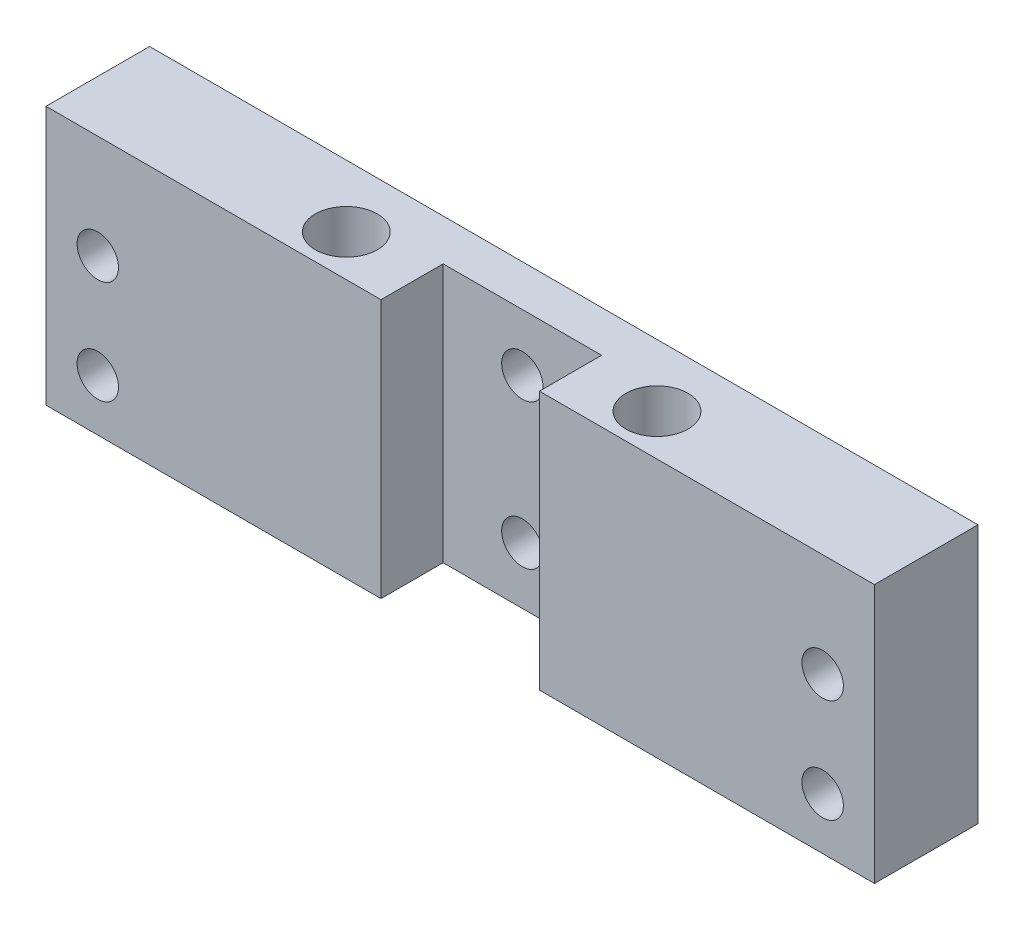
SolidWorks part; units mm, degrees
ref_plane "Plan de face" through (0, 0, 0) normal (0, 0, 1) x (1, 0, 0)
ref_plane "Plan de dessus" through (0, 0, 0) normal (0, 1, 0) x (1, 0, 0)
ref_plane "Plan de droite" through (0, 0, 0) normal (1, 0, 0) x (0, 0, -1)
sketch "Esquisse1" plane through (0, 0, 0) normal (0, 0, 1) x (1, 0, 0)
  line L0 (5, 25) -> (5, 0) construction
  line L1 (0, 0) -> (80, 0)
  line L2 (0, 0) -> (0, 25)
  line L3 (0, 25) -> (80, 25)
  line L4 (80, 0) -> (80, 25)
  line L5 (75, 0) -> (75, 25) construction
  line L6 (40, 25) -> (40, 0) construction
  circle A0 centre (5, 15) radius 2
  circle A1 centre (5, 5) radius 2
  circle A3 centre (75, 15) radius 2
  circle A4 centre (75, 5) radius 2
  circle A6 centre (40, 19.5) radius 2
  circle A7 centre (40, 5.5) radius 2
  point P29 (40, 12.5)
  dimension "D5" = 4
  dimension "D11" = 4
  dimension "D12" = 14
  dimension "D8" = 4
  dimension "D1" = 80
  dimension "D2" = 25
  dimension "D3" = 5
  dimension "D4" = 5
  dimension "D6" = 10
  dimension "D7" = 10
  dimension "D9" = 10
  dimension "D10" = 10
  dimension "D13" = 7
extrude "Boss.-Extru.1" add sketch "Esquisse1" along normal blind 10
sketch "Esquisse2" plane through (0, 0, 10) normal (0, 0, 1) x (1, 0, 0)
  line L0 (80, 25) -> (0, 25) construction
  line L1 (32.35, 25) -> (47.65, 25)
  line L2 (32.35, 25) -> (32.35, 0)
  line L3 (32.35, 0) -> (47.65, 0)
  line L4 (47.65, 25) -> (47.65, 0)
  line L5 (0, 0) -> (80, 0) construction
  line L6 (40, 25) -> (40, 0) construction
  dimension "D1" = 15.3
extrude "Enlèv. mat.-Extru.1" cut sketch "Esquisse2" against normal blind 6
sketch "Esquisse3" plane through (0, 25, 0) normal (0, 1, 0) x (1, 0, 0)
  line L0 (25, 0) -> (25, -10) construction
  line L1 (80, 0) -> (0, 0) construction
  line L2 (32.35, -10) -> (0, -10) construction
  line L3 (55, -10) -> (55, 0) construction
  line L4 (80, -10) -> (47.65, -10) construction
  line L5 (40, 0) -> (40, -4) construction
  line L6 (47.65, -4) -> (32.35, -4) construction
  circle A0 centre (55, -6) radius 3
  circle A1 centre (25, -6) radius 3
  dimension "D2" = 6
  dimension "D1" = 30
  dimension "D3" = 4
  dimension "D4" = 4
extrude "Enlèv. mat.-Extru.2" cut sketch "Esquisse3" against normal blind 15
